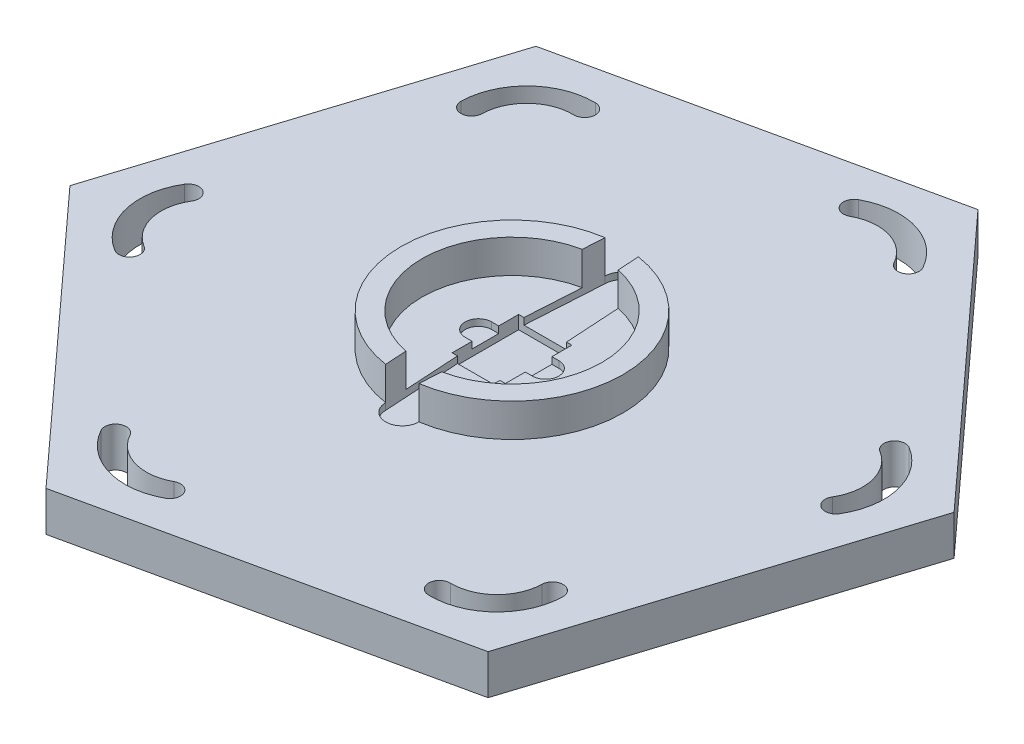
SolidWorks part; units mm, degrees
ref_plane "Plan de face" through (0, 0, 0) normal (0, 0, 1) x (1, 0, 0)
ref_plane "Plan de dessus" through (0, 0, 0) normal (0, 1, 0) x (1, 0, 0)
ref_plane "Plan de droite" through (0, 0, 0) normal (1, 0, 0) x (0, 0, -1)
sketch "Esquisse1" plane through (0, 0, 0) normal (0, 1, 0) x (1, 0, 0)
  line L7 (-37.6218, 41.2204) -> (-54.5089, -11.9712)
  line L8 (-54.5089, -11.9712) -> (-16.887, -53.1917)
  line L9 (-16.887, -53.1917) -> (37.6218, -41.2204)
  line L10 (37.6218, -41.2204) -> (54.5089, 11.9712)
  line L11 (54.5089, 11.9712) -> (16.887, 53.1917)
  line L12 (16.887, 53.1917) -> (-37.6218, 41.2204)
  circle A0 centre (0, 0) radius 48.3311 construction
  point P0 (0, 0)
extrude "Boss.-Extru.1" add sketch "Esquisse1" along normal blind 6
sketch "Esquisse2" plane through (0, 6, 0) normal (0, 1, 0) x (1, 0, 0)
  line L1 (4, -5) -> (-4, -5)
  line L2 (4, -5) -> (4, 5)
  line L3 (4, 5) -> (-4, 5)
  line L4 (-4, -5) -> (-4, 5)
  line L5 (4, -5) -> (-4, 5) construction
  line L6 (4, 5) -> (-4, -5) construction
  point P0 (0, 0)
  dimension "D1" = 10
  dimension "D2" = 8
extrude "Enlèv. mat.-Extru.1" cut sketch "Esquisse2" against normal blind 2
sketch "Esquisse5" plane through (0, 6, 0) normal (0, 1, 0) x (1, 0, 0)
  line L0 (0, 0) -> (0, 16.5) construction
  line L1 (-2.5, 16.5) -> (-3.5, 0)
  line L2 (2.5, 16.5) -> (3.5, 0)
  line L3 (-3.3, 0) -> (3.3, 0) construction
  line L4 (2.5, -16.5) -> (3.5, 0)
  line L5 (-2.5, -16.5) -> (-3.5, 0)
  circle A0 centre (0, 0) radius 3.5
  arc A1 (-2.5, 16.5) -> (2.5, 16.5) centre (0, 16.5) cw
  arc A2 (-2.5, -16.5) -> (2.5, -16.5) centre (0, -16.5) ccw
  dimension "D1" = 16.5
extrude "Enlèv. mat.-Extru.2" cut sketch "Esquisse5" against normal blind 1 contours L4 L2 A1 L1 L5 A2
sketch "Esquisse6" plane through (0, 6, 0) normal (0, 1, 0) x (1, 0, 0)
  line L0 (-5.05, 0) -> (5.05, 0) construction
  line L1 (-5.05, 2) -> (5.05, 2)
  line L2 (-5.05, -2) -> (5.05, -2)
  arc A0 (-5.05, 2) -> (-5.05, -2) centre (-5.05, 0) ccw
  arc A1 (5.05, -2) -> (5.05, 2) centre (5.05, 0) ccw
  point P2 (0, 0)
extrude "Enlèv. mat.-Extru.3" cut sketch "Esquisse6" against normal blind 1
sketch "Esquisse7" plane through (0, 6, 0) normal (0, 1, 0) x (1, 0, 0)
  line L0 (-2.5, -16.5) -> (-3.197, -5) construction
  line L1 (2.5, -16.5) -> (3.197, -5) construction
  line L2 (2.5, 16.5) -> (3.197, 5) construction
  line L3 (2.5, -16.5) -> (3.197, -5) construction
  line L4 (-2.5, 16.5) -> (-3.197, 5) construction
  line L5 (-2.5, -16.5) -> (-3.197, -5) construction
  line L6 (-2.5, 16.5) -> (-2.6964, 13.2598)
  line L7 (2.5, 16.5) -> (2.6964, 13.2598)
  line L8 (-2.6964, -13.2598) -> (-2.5, -16.5)
  line L9 (2.6964, -13.2598) -> (2.5, -16.5)
  arc A0 (-2.5, 16.5) -> (-2.5, -16.5) centre (0, 0) ccw
  arc A1 (2.5, 16.5) -> (2.5, -16.5) centre (0, 0) cw
  arc A2 (2.6964, 13.2598) -> (2.6964, -13.2598) centre (0, 0) cw
  arc A3 (-2.6964, 13.2598) -> (-2.6964, -13.2598) centre (0, 0) ccw
extrude "Boss.-Extru.2" add sketch "Esquisse7" along normal blind 5
sketch "Esquisse8" plane through (0, 6, 0) normal (0, 1, 0) x (1, 0, 0)
  line L0 (0, 0) -> (-54.5089, -11.9712) construction
  arc A0 (-44.7132, -3.9872) -> (-41.8652, -15.6638) centre (-37.4508, -8.4015) ccw construction
  arc A1 (-46.0804, -3.1561) -> (-42.6963, -17.0311) centre (-37.4508, -8.4015) ccw
  arc A2 (-43.3459, -4.8182) -> (-41.0341, -14.2966) centre (-37.4508, -8.4015) ccw
  arc A3 (-43.3459, -4.8182) -> (-46.0804, -3.1561) centre (-44.7132, -3.9872) ccw
  arc A4 (-42.6963, -17.0311) -> (-41.0341, -14.2966) centre (-41.8652, -15.6638) ccw
  arc A5 (-25.8096, 36.7292) -> (-34.4979, 28.4244) centre (-26.0013, 28.2326) ccw construction
  arc A6 (-25.7735, 38.3288) -> (-36.0975, 28.4605) centre (-26.0013, 28.2326) ccw
  arc A7 (-25.8457, 35.1296) -> (-32.8983, 28.3883) centre (-26.0013, 28.2326) ccw
  arc A8 (-25.8457, 35.1296) -> (-25.7735, 38.3288) centre (-25.8096, 36.7292) ccw
  arc A9 (-36.0975, 28.4605) -> (-32.8983, 28.3883) centre (-34.4979, 28.4244) ccw
  arc A10 (18.9036, 40.7163) -> (7.3673, 44.0882) centre (11.4495, 36.6341) ccw construction
  arc A11 (20.3069, 41.4848) -> (6.5988, 45.4916) centre (11.4495, 36.6341) ccw
  arc A12 (17.5003, 39.9478) -> (8.1358, 42.6849) centre (11.4495, 36.6341) ccw
  arc A13 (17.5003, 39.9478) -> (20.3069, 41.4848) centre (18.9036, 40.7163) ccw
  arc A14 (6.5988, 45.4916) -> (8.1358, 42.6849) centre (7.3673, 44.0882) ccw
  arc A15 (44.7132, 3.9872) -> (41.8652, 15.6638) centre (37.4508, 8.4015) ccw construction
  arc A16 (46.0804, 3.1561) -> (42.6963, 17.0311) centre (37.4508, 8.4015) ccw
  arc A17 (43.3459, 4.8182) -> (41.0341, 14.2966) centre (37.4508, 8.4015) ccw
  arc A18 (43.3459, 4.8182) -> (46.0804, 3.1561) centre (44.7132, 3.9872) ccw
  arc A19 (42.6963, 17.0311) -> (41.0341, 14.2966) centre (41.8652, 15.6638) ccw
  arc A20 (25.8096, -36.7292) -> (34.4979, -28.4244) centre (26.0013, -28.2326) ccw construction
  arc A21 (25.7735, -38.3288) -> (36.0975, -28.4605) centre (26.0013, -28.2326) ccw
  arc A22 (25.8457, -35.1296) -> (32.8983, -28.3883) centre (26.0013, -28.2326) ccw
  arc A23 (25.8457, -35.1296) -> (25.7735, -38.3288) centre (25.8096, -36.7292) ccw
  arc A24 (36.0975, -28.4605) -> (32.8983, -28.3883) centre (34.4979, -28.4244) ccw
  arc A25 (-18.9036, -40.7163) -> (-7.3673, -44.0882) centre (-11.4495, -36.6341) ccw construction
  arc A26 (-20.3069, -41.4848) -> (-6.5988, -45.4916) centre (-11.4495, -36.6341) ccw
  arc A27 (-17.5003, -39.9478) -> (-8.1358, -42.6849) centre (-11.4495, -36.6341) ccw
  arc A28 (-17.5003, -39.9478) -> (-20.3069, -41.4848) centre (-18.9036, -40.7163) ccw
  arc A29 (-6.5988, -45.4916) -> (-8.1358, -42.6849) centre (-7.3673, -44.0882) ccw
  point P7 (-45.7075, -10.4153)
  point P17 (-31.8737, 34.3762)
  point P25 (13.8338, 44.7915)
  point P33 (45.7075, 10.4153)
  point P41 (31.8737, -34.3762)
  point P49 (-13.8338, -44.7915)
  point P54 (0, 0)
  dimension "D1" = 6
extrude "Enlèv. mat.-Extru.4" cut sketch "Esquisse8" against normal blind 6
